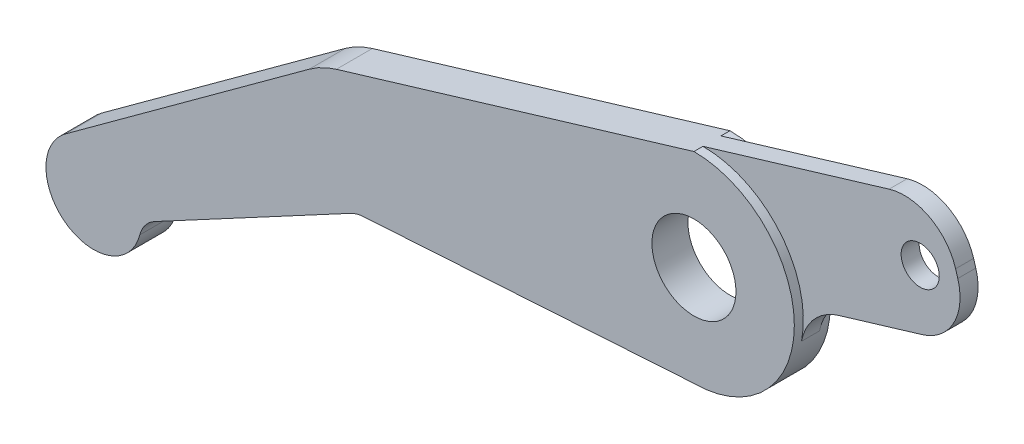
SolidWorks part; units mm, degrees
ref_plane "Front Plane" through (0, 0, 0) normal (0, 0, 1) x (1, 0, 0)
ref_plane "Top Plane" through (0, 0, 0) normal (0, 1, 0) x (1, 0, 0)
ref_plane "Right Plane" through (0, 0, 0) normal (1, 0, 0) x (0, 0, -1)
sketch "Sketch1" plane through (0, 0, 0) normal (0, 0, 1) x (1, 0, 0)
  line L0 (-96.9155, -1.122) -> (-15.7224, 58.1409)
  line L1 (-6.6863, 62.6332) -> (112.4461, 98.4716)
  line L2 (112.4461, 31.5711) -> (2.1763, 24.613)
  line L3 (-1.9219, 23.4454) -> (-67.2042, -11.5524)
  circle A0 centre (112.4461, 65.0213) radius 14
  arc A2 (112.4461, 31.5711) -> (112.4461, 98.4716) centre (112.4461, 65.0213) ccw
  arc A3 (-96.9155, -1.122) -> (-72.1704, -17.8891) centre (-87.5535, -13.9485) ccw
  circle A6 centre (96.2592, 82.4764) radius 3.1426
  circle A7 centre (119.4692, 87.7672) radius 3.1426
  circle A8 centre (135.6562, 70.3121) radius 3.1426
  circle A9 centre (128.6331, 47.5662) radius 3.1426
  circle A10 centre (105.4231, 42.2755) radius 3.1426
  circle A11 centre (89.2361, 59.7306) radius 3.1426
  arc A12 (-15.7224, 58.1409) -> (-6.6863, 62.6332) centre (1.9479, 33.9318) cw
  arc A13 (-67.2042, -11.5524) -> (-72.1704, -17.8891) centre (-62.4758, -20.3725) ccw
  arc A14 (2.1763, 24.613) -> (-1.9219, 23.4454) centre (2.8065, 14.6253) ccw
  point P25 (112.4461, 65.0213)
  point P29 (-71.6737, -13.9485)
  dimension "D3" = 6.2853
  dimension "D5" = 29.972
  dimension "D6" = 10.0076
  dimension "D7" = 28
  dimension "D8" = 33.4503
  dimension "D9" = 15.8798
  dimension "D1" = 199.9996
  dimension "D4" = 17.4551
  dimension "D10" = 1.9479
  dimension "D11" = 2.1763
  dimension "D12" = 2.8065
  dimension "D13" = 89.2361
  dimension "D14" = 96.2592
  dimension "D15" = 1.9219
  dimension "D16" = 6.6863
  dimension "D17" = 14.6253
  dimension "D2" = 6
extrude "Boss-Extrude1" add sketch "Sketch1" against normal blind 12 contours A14 L2 A2 L1 A12 L0 A3 A13 L3 A11 A10 A9 A8 A7 A6 A0 | A7 | A8 | A9 | A11 | A6
sketch "Sketch2" plane through (0, 0, 0) normal (0, 0, 1) x (1, 0, 0)
  line L0 (112.4461, 98.4716) -> (191.4967, 122.2522)
  line L1 (191.4967, 122.2522) -> (202.4723, 85.7673)
  line L2 (202.4723, 85.7673) -> (145.6949, 68.6871)
  line L3 (-6.6863, 62.6332) -> (112.4461, 98.4716) construction
  line L4 (179.335, 118.5936) -> (190.3107, 82.1088) construction
  circle A0 centre (112.4461, 65.0213) radius 14 construction
  circle A1 centre (112.4461, 65.0213) radius 14
  arc A2 (112.4461, 31.5711) -> (112.4461, 98.4716) centre (112.4461, 65.0213) ccw construction
  circle A3 centre (184.8229, 100.3512) radius 6.35
  arc M7 (112.4461, 31.5711) -> (112.4461, 98.4716) centre (112.4461, 65.0213) ccw
  dimension "D4" = 12.7
  dimension "D1" = 82.55
  dimension "D2" = 38.1
  dimension "D3" = 12.7
extrude "Boss-Extrude2" add sketch "Sketch2" against normal blind 9 contours L4 L0 L2 A3 M7 | L0 L4 A3 L2 L1
fillet "Fillet1" radius 17.78 3 edges at (145.6949, 68.6871, -4.5) (191.4967, 122.2522, -4.5) (202.4723, 85.7673, -4.5)
sketch "Sketch4" plane through (0, 0, 0) normal (0, 0, 1) x (1, 0, 0)
  line L3 (174.4704, 117.1302) -> (112.4461, 98.4716)
  line L4 (197.3503, 102.7936) -> (196.6186, 105.2259)
  line L5 (157.6132, 72.2725) -> (185.446, 80.6454)
  line L6 (174.4704, 117.1302) -> (112.4461, 98.4716)
  line L7 (197.3503, 102.7936) -> (196.6186, 105.2259)
  line L8 (157.6132, 72.2725) -> (185.446, 80.6454)
  arc A4 (196.6186, 105.2259) -> (174.4704, 117.1302) centre (179.5924, 100.104) ccw
  arc A5 (185.446, 80.6454) -> (197.3503, 102.7936) centre (180.3241, 97.6716) ccw
  arc A6 (157.6132, 72.2725) -> (145.2818, 58.6388) centre (162.7352, 55.2462) ccw
  arc A7 (145.2818, 58.6388) -> (112.4461, 98.4716) centre (112.4461, 65.0213) ccw
  arc A8 (196.6186, 105.2259) -> (174.4704, 117.1302) centre (179.5924, 100.104) ccw
  arc A9 (185.446, 80.6454) -> (197.3503, 102.7936) centre (180.3241, 97.6716) ccw
  arc A10 (157.6132, 72.2725) -> (145.2818, 58.6388) centre (162.7352, 55.2462) ccw
  arc A11 (145.2818, 58.6388) -> (112.4461, 98.4716) centre (112.4461, 65.0213) ccw
  dimension "D1" = 0
extrude "Cut-Extrude2" cut sketch "Sketch4" against normal blind 3
